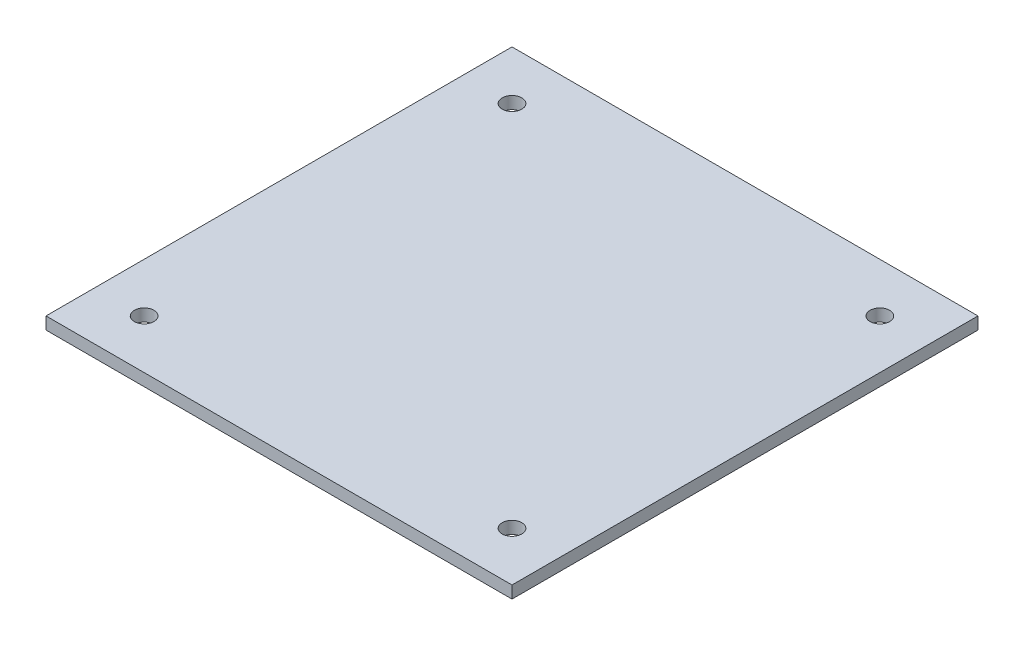
SolidWorks part; units mm, degrees
ref_plane "前视基准面" through (0, 0, 0) normal (0, 0, 1) x (1, 0, 0)
ref_plane "上视基准面" through (0, 0, 0) normal (0, 1, 0) x (1, 0, 0)
ref_plane "右视基准面" through (0, 0, 0) normal (1, 0, 0) x (0, 0, -1)
sketch "草图1" plane through (0, 0, 0) normal (0, 1, 0) x (1, 0, 0)
  line L1 (38, -38) -> (-38, -38)
  line L2 (38, -38) -> (38, 38)
  line L3 (38, 38) -> (-38, 38)
  line L4 (-38, -38) -> (-38, 38)
  line L5 (38, -38) -> (-38, 38) construction
  line L6 (38, 38) -> (-38, -38) construction
  point P0 (0, 0)
  dimension "D1" = 76
  dimension "D2" = 76
extrude "凸台-拉伸1" add sketch "草图1" along normal blind 2
sketch "草图2" plane through (0, 2, 0) normal (0, 1, 0) x (1, 0, 0)
  line L1 (30, -30) -> (-30, -30) construction
  line L2 (30, -30) -> (30, 30) construction
  line L3 (30, 30) -> (-30, 30) construction
  line L4 (-30, -30) -> (-30, 30) construction
  line L5 (30, -30) -> (-30, 30) construction
  line L6 (30, 30) -> (-30, -30) construction
  circle A0 centre (-30, 30) radius 1.6
  point P0 (0, 0)
  dimension "D3" = 3.2
  dimension "D1" = 60
  dimension "D2" = 60
extrude "切除-拉伸1" cut sketch "草图2" against normal blind 2
pattern_linear "阵列(线性)1" count 2 spacing 60 along (1, 0, 0) count 2 spacing 60 along (0, 0, 1) of "切除-拉伸1"
